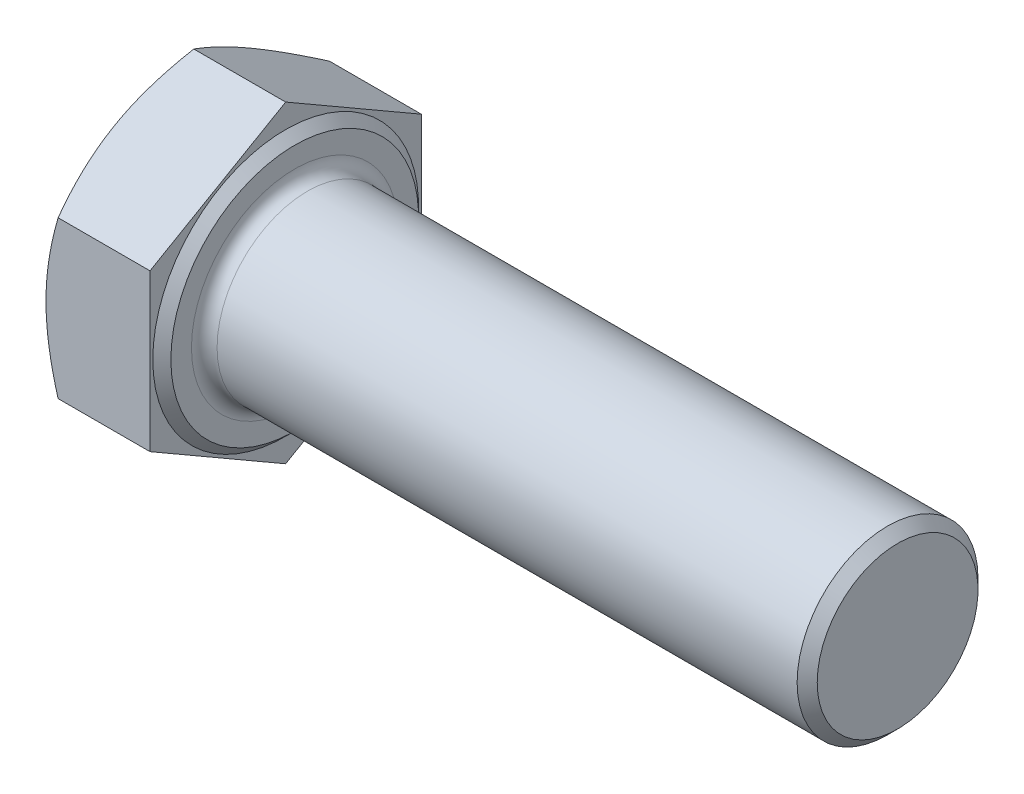
SolidWorks part; units mm, degrees
ref_plane "前视基准面" through (0, 0, 0) normal (0, 0, 1) x (1, 0, 0)
ref_plane "上视基准面" through (0, 0, 0) normal (0, 1, 0) x (1, 0, 0)
ref_plane "右视基准面" through (0, 0, 0) normal (1, 0, 0) x (0, 0, -1)
sketch "草图1" plane through (0, 0, 0) normal (0, 0, 1) x (1, 0, 0)
  line L0 (0, 0) -> (47.5, 0) construction
  line L1 (0, 0) -> (0, 10.015)
  line L2 (0, 10.015) -> (7.5, 10.015)
  line L3 (7.5, 10.015) -> (7.5, 0)
  line L4 (7.5, 6) -> (47.5, 6)
  line L5 (47.5, 6) -> (47.5, 0)
  line L6 (0, 9) -> (0.586, 10.015)
  line L7 (44, 6) -> (44, 0)
  line L8 (12.8, 6) -> (12.8, 0)
  line L9 (7.5, 5.4317) -> (47.5, 5.4317)
  line L10 (47.5, 5.0528) -> (7.5, 5.0528)
  line L11 (6.9, 8.815) -> (7.5, 8.215)
  line L12 (6.9, 10.015) -> (6.9, 0)
  line L13 (7.4, 8.315) -> (7.4, 0) construction
  arc A0 (7.5, 6.85) -> (8.35, 6) centre (8.35, 6.85) ccw
  point P12 (45.75, 0)
  point P13 (2.38, 10.015)
  point P14 (7.5, 6.85)
  point P24 (7.5, 8.315)
  dimension "D1" = 0.1
  dimension "r" = 0.85
  dimension "k" = 7.5
  dimension "D2" = 45
  dimension "β" = 30
  dimension "e" = 20.03
  dimension "s" = 18
  dimension "d" = 12
  dimension "l" = 40
  dimension "D52" = 3.5
  dimension "P" = 1.75
  dimension "kw" = 5.12
  dimension "da" = 13.7
  dimension "a" = 5.3
  dimension "ds" = 10.8634
  dimension "D61" = 10.1056
  dimension "dw" = 16.63
  dimension "c" = 0.6
sketch "草图2" plane through (0, 0, 0) normal (1, 0, 0) x (0, 0, -1)
  line L1 (0, 10.3923) -> (-9, 5.1962)
  line L2 (-9, 5.1962) -> (-9, -5.1962)
  line L3 (-9, -5.1962) -> (0, -10.3923)
  line L4 (0, -10.3923) -> (9, -5.1962)
  line L5 (9, -5.1962) -> (9, 5.1962)
  line L6 (9, 5.1962) -> (0, 10.3923)
  circle A0 centre (0, 0) radius 9 construction
sketch "草图3" plane through (0, 0, 0) normal (1, 0, 0) x (0, 0, -1)
  line L0 (9, 5.1962) -> (0, 10.3923) construction
  line L1 (0, 10.3923) -> (-9, 5.1962) construction
  line L2 (-9, 5.1962) -> (-9, -5.1962) construction
  line L3 (9, -5.1962) -> (9, 5.1962) construction
  line L4 (0, -10.3923) -> (9, -5.1962) construction
  line L5 (-9, -5.1962) -> (0, -10.3923) construction
  line L6 (9, 5.1962) -> (0, 10.3923)
  line L7 (0, 10.3923) -> (-9, 5.1962)
  line L8 (-9, 5.1962) -> (-9, -5.1962)
  line L9 (9, -5.1962) -> (9, 5.1962)
  line L10 (0, -10.3923) -> (9, -5.1962)
  line L11 (-9, -5.1962) -> (0, -10.3923)
extrude "凸台-拉伸1" add sketch "草图3" along normal up to vertex (7.5 mm away) up to point (7.5, 10.015, 0)
sketch "草图4" plane through (0, 0, 0) normal (-1, 0, 0) x (0, 0, 1)
  circle A0 centre (0, 0) radius 9 construction
  circle A1 centre (0, 0) radius 9
  circle A2 centre (0, 0) radius 20.03
  dimension "D1" = 40.06
extrude "切除-拉伸1" cut sketch "草图4" against normal blind 0.9375 draft 60
sketch "草图5" plane through (0, 0, 0) normal (0, 0, 1) x (1, 0, 0)
  line L0 (7.5, 6) -> (47.5, 6) construction
  line L1 (47.5, 6) -> (47.5, 0) construction
  line L2 (0, 0) -> (47.5, 0) construction
  line L3 (8.35, 6) -> (47.5, 6)
  line L4 (47.5, 6) -> (47.5, 0)
  line L5 (7.5, 0) -> (47.5, 0)
  line L6 (7.5, 6.85) -> (7.5, 0)
  arc A0 (7.5, 6.85) -> (8.35, 6) centre (8.35, 6.85) ccw construction
  arc A1 (7.5, 6.85) -> (8.35, 6) centre (8.35, 6.85) ccw
revolve "旋转1" add sketch "草图5" angle 360 about L5
cosmetic thread "装饰螺纹线2" parameters "D1"=34.7, "D2"=10.1056
chamfer "倒角2" distance 0.6667 angle 45 1 edges at (47.5, 0, 6)
sketch "草图7" plane through (0, 0, 0) normal (0, 0, 1) x (1, 0, 0)
  line L0 (7.5, 8.215) -> (6.9, 8.815)
  line L1 (6.9, 8.815) -> (6.9, 20.03)
  line L2 (6.9, 20.03) -> (7.5, 20.03)
  line L3 (7.5, 20.03) -> (7.5, 8.215)
  line L4 (0, 0) -> (47.5, 0) construction
  line L5 (0, 0) -> (47.5, 0) construction
  dimension "D1" = 40.06
revolve "切除-旋转1" cut sketch "草图7" angle 360 mid plane about L5
sketch "草图6" [suppressed] plane through (0, 0, 0) normal (0, 0, 1) x (1, 0, 0)
  line L0 (9.3, 0) -> (9.3, 4) construction
  line L1 (9.3, 4) -> (75.3, 4)
  line L2 (75.3, 4) -> (75.3, 0)
  line L3 (9.3, 4) -> (5.9719, 3.5984)
  line L5 (5.3, 3.5941) -> (75.3, 3.5941) construction
  line L6 (5.3, 7.19) -> (5.3, 0) construction
  line L7 (5.3, 4.1941) -> (5.3, 0)
  line L8 (5.3, 0) -> (75.3, 0)
  arc A0 (5.9719, 3.5984) -> (5.3, 4.1941) centre (5.9, 4.1941) cw
  arc A1 (5.3, 4.6) -> (5.9, 4) centre (5.9, 4.6) ccw construction
revolve "旋转2" [suppressed] add sketch "草图6" angle 360 about L8
cosmetic thread "装饰螺纹线1" [suppressed] parameters "D1"=34.7, "D2"=10.1056
chamfer "倒角1" [suppressed] distance 0.6667 angle 45
sketch "草图8" [suppressed] plane through (0, 0, 0) normal (0, 0, 1) x (1, 0, 0)
  line L0 (5.3, 5.715) -> (4.7, 6.315)
  line L1 (4.7, 6.315) -> (4.7, 14.38)
  line L2 (4.7, 14.38) -> (5.3, 14.38)
  line L3 (5.3, 14.38) -> (5.3, 5.715)
  line L4 (0, 0) -> (75.3, 0) construction
  line L5 (0, 0) -> (75.3, 0) construction
  dimension "D1" = 40.06
revolve "切除-旋转2" [suppressed] cut sketch "草图8" angle 360 mid plane about L5
